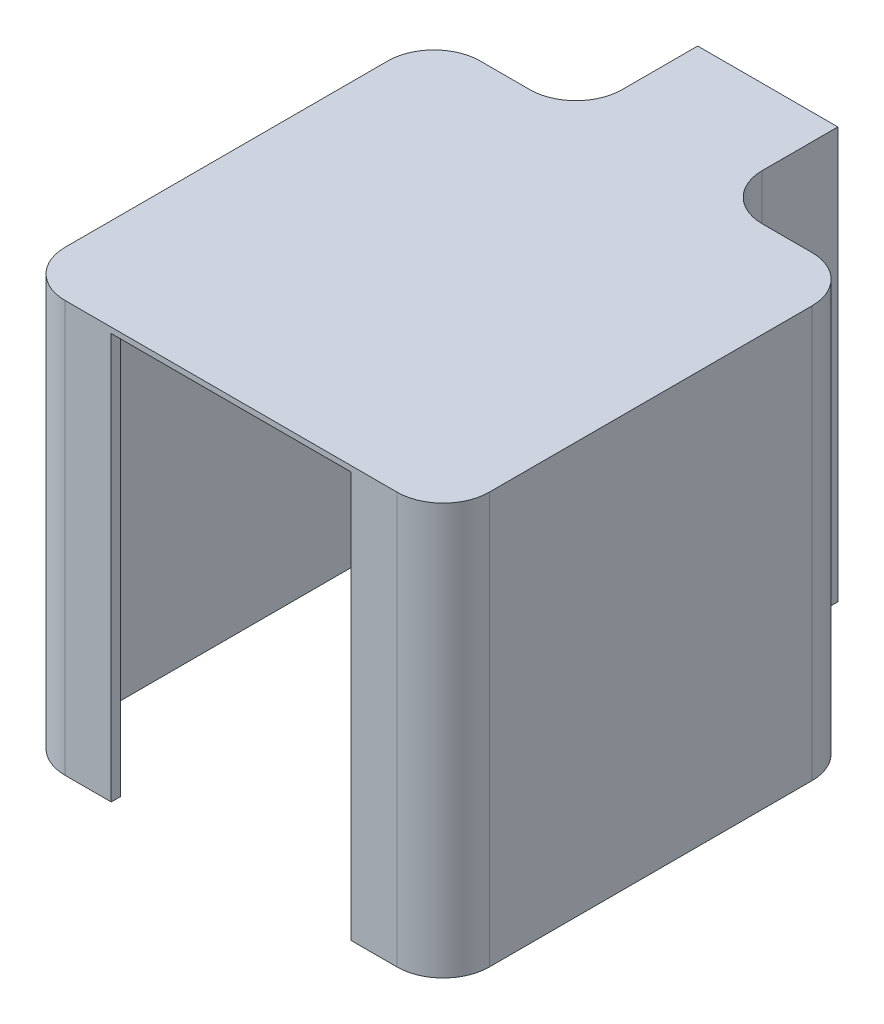
SolidWorks part; units mm, degrees
ref_plane "Front Plane" through (0, 0, 0) normal (0, 0, 1) x (1, 0, 0)
ref_plane "Top Plane" through (0, 0, 0) normal (0, 1, 0) x (1, 0, 0)
ref_plane "Right Plane" through (0, 0, 0) normal (1, 0, 0) x (0, 0, -1)
sketch "Sketch1" plane through (0, 0, 0) normal (0, 1, 0) x (1, 0, 0)
  line L0 (33, 107.5) -> (110, 107.5)
  line L1 (-110, 107.5) -> (-33, 107.5)
  line L2 (-110, 107.5) -> (-110, -107.5)
  line L3 (-110, -107.5) -> (-65, -107.5)
  line L4 (110, 107.5) -> (110, -107.5)
  line L5 (-110, 107.5) -> (110, -107.5) construction
  line L6 (-110, -107.5) -> (110, 107.5) construction
  line L8 (-33, 107.5) -> (-33, 173.5)
  line L9 (-33, 173.5) -> (33, 173.5)
  line L10 (33, 107.5) -> (33, 173.5)
  line L11 (5, 107.5) -> (33, 173.5) construction
  line L12 (-33, 173.5) -> (5, 107.5) construction
  line L13 (-115, 112.5) -> (-115, -112.5)
  line L14 (-115, -112.5) -> (-65, -112.5)
  line L15 (115, 112.5) -> (115, -112.5)
  line L16 (38, 112.5) -> (115, 112.5)
  line L17 (38, 112.5) -> (38, 178.5)
  line L18 (-38, 178.5) -> (38, 178.5)
  line L19 (-38, 112.5) -> (-38, 178.5)
  line L20 (-115, 112.5) -> (-38, 112.5)
  line L21 (-65, -107.5) -> (-65, -112.5)
  line L22 (65, -107.5) -> (65, -112.5)
  line L23 (65, -112.5) -> (115, -112.5)
  line L24 (-115, -112.5) -> (115, -112.5) construction
  line L25 (65, -107.5) -> (110, -107.5)
  line L26 (-110, -107.5) -> (110, -107.5) construction
  point P0 (0, 0)
  point P6 (5, 107.5)
  dimension "D1" = 215
  dimension "D2" = 220
  dimension "D3" = 66
  dimension "D4" = 66
  dimension "D5" = 33
  dimension "D7" = 50
  dimension "D8" = 50
  dimension "D6" = 5
extrude "Boss-Extrude1" add sketch "Sketch1" along normal blind 220
fillet "Fillet1" radius 25 4 edges at (33, 110, -107.5) (38, 110, -112.5) (-33, 110, -107.5) (-38, 110, -112.5)
sketch "Sketch2" plane through (0, 220, 0) normal (0, 1, 0) x (1, 0, 0)
  line L0 (-115, -112.5) -> (115, -112.5)
  line L1 (115, -112.5) -> (115, 112.5)
  line L2 (115, 112.5) -> (63, 112.5)
  line L3 (38, 137.5) -> (38, 178.5)
  line L4 (38, 178.5) -> (-38, 178.5)
  line L5 (-38, 178.5) -> (-38, 137.5)
  line L6 (-63, 112.5) -> (-115, 112.5)
  line L7 (-115, 112.5) -> (-115, -112.5)
  arc A0 (63, 112.5) -> (38, 137.5) centre (63, 137.5) cw
  arc A1 (-38, 137.5) -> (-63, 112.5) centre (-63, 137.5) cw
extrude "Boss-Extrude2" add sketch "Sketch2" along normal blind 3
fillet "Fillet2" radius 25 8 edges at (115, 111.5, 112.5) (110, 110, 107.5) (-115, 111.5, 112.5) (-110, 110, 107.5) (115, 111.5, -112.5) (110, 110, -107.5) (-110, 110, -107.5) (-115, 111.5, -112.5)
